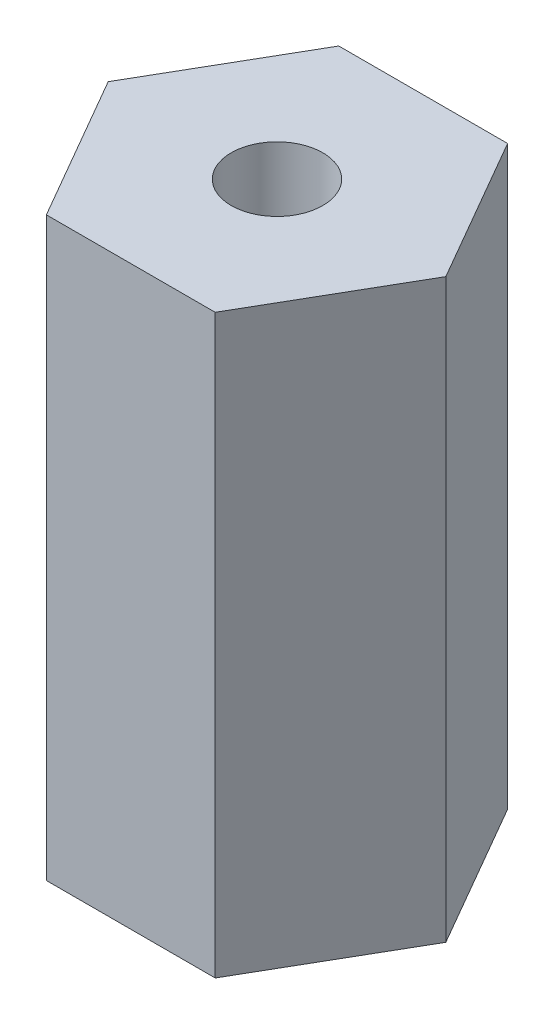
SolidWorks part; units mm, degrees
material "PETG"
ref_plane "Front Plane" through (0, 0, 0) normal (0, 0, 1) x (1, 0, 0)
ref_plane "Top Plane" through (0, 0, 0) normal (0, 1, 0) x (1, 0, 0)
ref_plane "Right Plane" through (0, 0, 0) normal (1, 0, 0) x (0, 0, -1)
sketch "Sketch2" plane through (0, 0, 0) normal (0, 1, 0) x (1, 0, 0)
  line L1 (7.3208, 0) -> (3.6604, 6.34)
  line L2 (3.6604, 6.34) -> (-3.6604, 6.34)
  line L3 (-3.6604, 6.34) -> (-7.3208, 0)
  line L4 (-7.3208, 0) -> (-3.6604, -6.34)
  line L5 (-3.6604, -6.34) -> (3.6604, -6.34)
  line L6 (3.6604, -6.34) -> (7.3208, 0)
  circle A0 centre (0, 0) radius 6.34 construction
  dimension "D1" = 12.68
extrude "Boss-Extrude1" add sketch "Sketch2" along normal mid plane 25
sketch "Sketch3" plane through (0, 0, 0) normal (0, 1, 0) x (1, 0, 0)
  circle A0 centre (0, 0) radius 1.985
  dimension "D1" = 3.97
extrude "Cut-Extrude1" cut sketch "Sketch3" against normal through all both and the other way through all
equation "\"tol_dia_id_intfc\" = 0.0200mm ' For hole diameters - Interference fit"
equation "\"tol_dia_id_slip\"  = 0.0300mm ' For hole diameters - Slip fit"
equation "\"tol_dia_id_clear\" = 0.0500mm ' For hole diameters - Clearance fit"
equation "\"tol_dia_od_intfc\" = 0.0200mm ' For shaft diameters - Interference fit"
equation "\"tol_dia_od_slip\"  = 0.0300mm ' For shaft diameters - Slip fit"
equation "\"tol_dia_od_clear\" = 0.0500mm ' For shaft diameters - Clearance fit"
equation "\"tol_general_intfc\"= 0.0030mm ' For general parts (Horiz) - Interference fit"
equation "\"tol_general_slip\" = 0.0050mm ' For general parts (Horiz) - Slip fit"
equation "\"tol_general_clear\"= 0.0100mm ' For general parts (Horiz) - Clearance fit"
equation "\"tol_layer_intfc\"  = 0.0030mm ' For all parts (Vert) - Interference fit"
equation "\"tol_layer_slip\"   = 0.0050mm ' For all parts (Vert) - Slip fit"
equation "\"tol_layer_clear\"  = 0.0100mm ' For all parts (Vert) - Clearance fit"
equation "\"tol_corner_rad\"   = 0.100mm ' For corners that fit into other parts"
equation "\"D1@Sketch2\"=12.7 - \"tol_general_clear\"*2"
equation "\"D1@Sketch3\"=3.95 + \"tol_dia_id_intfc\""
